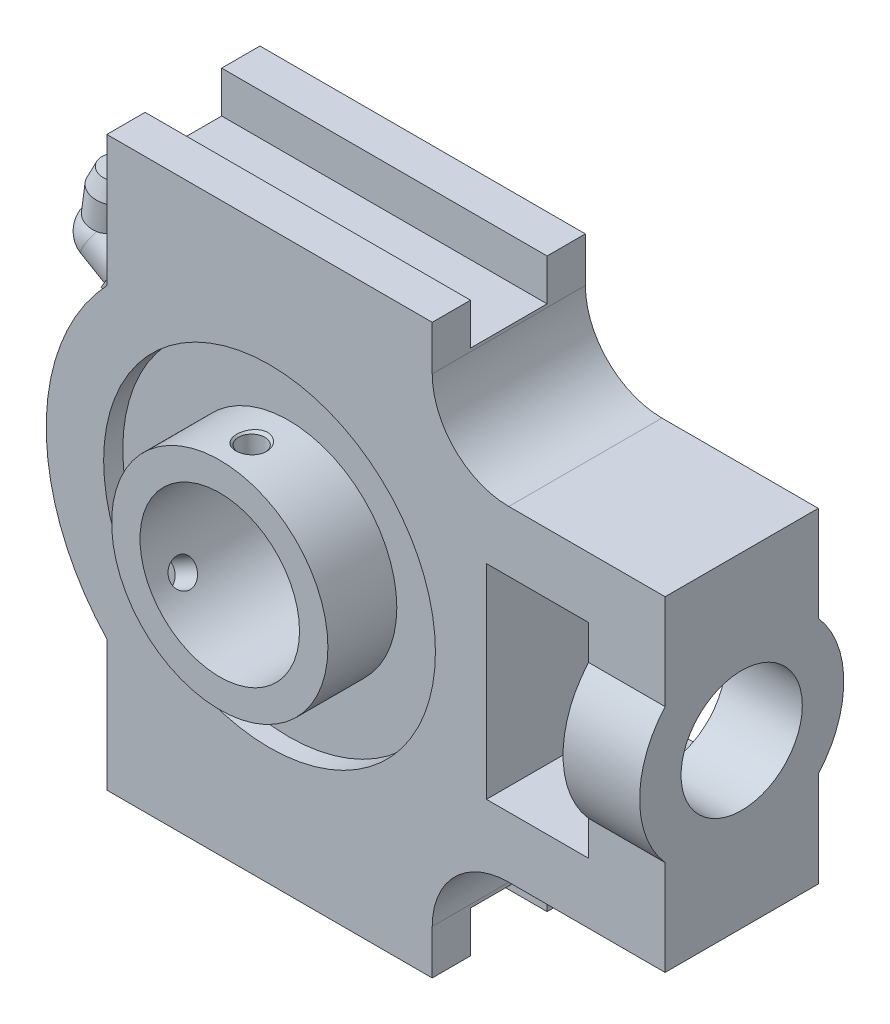
SolidWorks part; units mm, degrees
ref_plane "Front Plane" through (0, 0, 0) normal (0, 0, 1) x (1, 0, 0)
ref_plane "Top Plane" through (0, 0, 0) normal (0, 1, 0) x (1, 0, 0)
ref_plane "Right Plane" through (0, 0, 0) normal (1, 0, 0) x (0, 0, -1)
ref_plane "Plane1" through (0, 0, 0) normal (0.5, 0.866, 0) x (0.866, -0.5, 0)
sketch "Sketch1" plane through (0, 0, 0) normal (0.5, 0.866, 0) x (0.866, -0.5, 0)
  line L0 (-41.5, 2.8) -> (-37, 2.8)
  line L1 (-37, 2.8) -> (-37, 3.8)
  line L2 (-37, 3.8) -> (-34.5, 3.8)
  line L3 (-34.5, 3.8) -> (-34.5, -1.2)
  line L4 (-34.5, -1.2) -> (-45.5, -1.2)
  line L5 (-34.5, -1.2) -> (-45.5, -1.2) construction
  arc A0 (-45.5, -1.2) -> (-41.5, 2.8) centre (-41.5, -1.2) cw
revolve "Revolve1" add sketch "Sketch1" angle 360 about L5
ref_plane "Plane2" through (-30.3109, 17.5, 0) normal (0.866, -0.5, 0) x (0, 0, -1)
sketch "Sketch2" plane through (-30.3109, 17.5, 0) normal (0.866, -0.5, 0) x (0, 0, -1)
  line L0 (-5.2, -2.3094) -> (-1.2, -4.6188)
  line L1 (-1.2, -4.6188) -> (2.8, -2.3094)
  line L2 (2.8, -2.3094) -> (2.8, 2.3094)
  line L3 (2.8, 2.3094) -> (-1.2, 4.6188)
  line L4 (-1.2, 4.6188) -> (-5.2, 2.3094)
  line L5 (-5.2, 2.3094) -> (-5.2, -2.3094)
  circle A0 centre (-1.2, 0) radius 5.5
extrude "Cut-Extrude1" cut sketch "Sketch2" against normal blind 4 and the other way blind 4
ref_plane "Plane3" through (-38.013, 5.0045, 0) normal (0.9914, -0.1305, 0) x (0, 0, -1)
sketch "Sketch3" plane through (-38.013, 5.0045, 0) normal (0.9914, -0.1305, 0) x (0, 0, -1)
  line L0 (-1.2, 15.8814) -> (-4.5, 15.8814)
  line L1 (-4.5, 15.8814) -> (-4.5, 22.4814)
  line L2 (-4.5, 22.4814) -> (-3.6, 25.1814)
  line L3 (-3.6, 25.1814) -> (-1.2, 25.1814)
  line L4 (-1.2, 25.1814) -> (-1.2, 15.8814)
  line L5 (-1.2, 25.1814) -> (-1.2, 15.8814) construction
revolve "Revolve2" add sketch "Sketch3" angle 360 about L5
ref_plane "Plane4" through (0, 0, 0) normal (0, 0, 1) x (1, 0, 0)
sketch "Sketch4" plane through (0, 0, 0) normal (0, 0, 1) x (1, 0, 0)
  line L0 (-25.5, -23.9739) -> (-25.5, -44.5)
  line L1 (-25.5, -44.5) -> (25.5, -44.5)
  line L2 (25.5, -44.5) -> (25.5, -37.5)
  line L3 (37.5, -25.5) -> (62, -25.5)
  line L4 (62, -25.5) -> (62, 25.5)
  line L5 (62, 25.5) -> (37.5, 25.5)
  line L6 (25.5, 37.5) -> (25.5, 44.5)
  line L7 (25.5, 44.5) -> (-25.5, 44.5)
  line L8 (-25.5, 44.5) -> (-25.5, 23.9739)
  line L9 (34, 16) -> (34, -16)
  line L10 (34, -16) -> (50, -16)
  line L11 (50, -16) -> (50, 16)
  line L12 (50, 16) -> (34, 16)
  arc A0 (-25.5, 23.9739) -> (-25.5, -23.9739) centre (0, 0) ccw
  arc A1 (25.5, -37.5) -> (37.5, -25.5) centre (37.5, -37.5) cw
  arc A2 (37.5, 25.5) -> (25.5, 37.5) centre (37.5, 37.5) cw
extrude "Boss-Extrude1" add sketch "Sketch4" against normal blind 12 and the other way blind 12
ref_plane "Plane5" through (62, 0, 0) normal (1, 0, 0) x (0, 0, -1)
sketch "Sketch5" plane through (62, 0, 0) normal (1, 0, 0) x (0, 0, -1)
  circle A0 centre (0, 0) radius 16
  circle A1 centre (0, 0) radius 9.5
extrude "Boss-Extrude2" add sketch "Sketch5" against normal blind 12
ref_plane "Plane6" through (62, 0, 0) normal (1, 0, 0) x (0, 0, -1)
sketch "Sketch6" plane through (62, 0, 0) normal (1, 0, 0) x (0, 0, -1)
  circle A0 centre (0, 0) radius 9.5
extrude "Cut-Extrude2" cut sketch "Sketch6" against normal blind 12
ref_plane "Plane7" through (25.5, 0, 0) normal (1, 0, 0) x (0, 0, -1)
sketch "Sketch7" plane through (25.5, 0, 0) normal (1, 0, 0) x (0, 0, -1)
  line L0 (-6, 45.5) -> (-6, 38)
  line L1 (-6, 38) -> (6, 38)
  line L2 (6, 38) -> (6, 45.5)
  line L3 (6, 45.5) -> (-6, 45.5)
extrude "Cut-Extrude3" cut sketch "Sketch7" against normal blind 51 and the other way blind 51
ref_plane "Plane8" through (25.5, 0, 0) normal (1, 0, 0) x (0, 0, -1)
sketch "Sketch8" plane through (25.5, 0, 0) normal (1, 0, 0) x (0, 0, -1)
  line L0 (-6, -45.5) -> (6, -45.5)
  line L1 (6, -45.5) -> (6, -38)
  line L2 (6, -38) -> (-6, -38)
  line L3 (-6, -38) -> (-6, -45.5)
extrude "Cut-Extrude4" cut sketch "Sketch8" against normal blind 51 and the other way blind 51
ref_plane "Plane9" through (0, 0, 0) normal (1, 0, 0) x (0, 0, -1)
sketch "Sketch9" plane through (0, 0, 0) normal (1, 0, 0) x (0, 0, -1)
  line L0 (-19.8, 0) -> (-19.8, 26)
  line L1 (-19.8, 26) -> (14.3, 26)
  line L2 (14.3, 26) -> (14.3, 0)
  line L3 (14.3, 0) -> (-19.8, 0)
  line L4 (14.3, 0) -> (-19.8, 0) construction
revolve "Cut-Revolve1" cut sketch "Sketch9" angle 360 about L4
ref_plane "Plane10" through (0, 0, 0) normal (1, 0, 0) x (0, 0, -1)
sketch "Sketch10" plane through (0, 0, 0) normal (1, 0, 0) x (0, 0, -1)
  line L0 (-19.8, 12.5) -> (14.3, 12.5)
  line L1 (14.3, 12.5) -> (14.3, 16.95)
  line L2 (14.3, 16.95) -> (9, 16.95)
  line L3 (9, 16.95) -> (9, 26)
  line L4 (9, 26) -> (-9, 26)
  line L5 (-9, 26) -> (-9, 16.95)
  line L6 (-9, 16.95) -> (-19.8, 16.95)
  line L7 (-19.8, 16.95) -> (-19.8, 12.5)
  line L8 (50, 0) -> (-50, 0) construction
revolve "Revolve3" add sketch "Sketch10" angle 360 about L8
ref_plane "Plane11" through (0, 0, 14.8) normal (0, 0, 1) x (1, 0, 0)
sketch "Sketch11" plane through (0, 0, 14.8) normal (0, 0, 1) x (1, 0, 0)
  line L0 (0, 16.95) -> (2.5, 16.95)
  line L1 (2.5, 16.95) -> (2.067, 16.517)
  line L2 (2.067, 16.517) -> (2.067, 0)
  line L3 (2.067, 0) -> (0, 0)
  line L4 (0, 0) -> (0, 16.95)
  line L5 (0, 0) -> (0, 16.95) construction
revolve "Cut-Revolve2" cut sketch "Sketch11" angle 360 about L5
cosmetic thread "Cosmetic Thread1" parameters "D1"=4.45, "D2"=5
ref_plane "Plane12" through (0, 0, 14.8) normal (0, 0, 1) x (1, 0, 0)
sketch "Sketch12" plane through (0, 0, 14.8) normal (0, 0, 1) x (1, 0, 0)
  line L0 (-14.6791, -8.475) -> (-15.9291, -6.3099)
  line L1 (-15.9291, -6.3099) -> (-15.3376, -6.4684)
  line L2 (-15.3376, -6.4684) -> (-1.0335, 1.7901)
  line L3 (-1.0335, 1.7901) -> (0, 0)
  line L4 (0, 0) -> (-14.6791, -8.475)
  line L5 (0, 0) -> (-14.6791, -8.475) construction
revolve "Cut-Revolve3" cut sketch "Sketch12" angle 360 about L5
cosmetic thread "Cosmetic Thread2" parameters "D1"=4.45, "D2"=5
